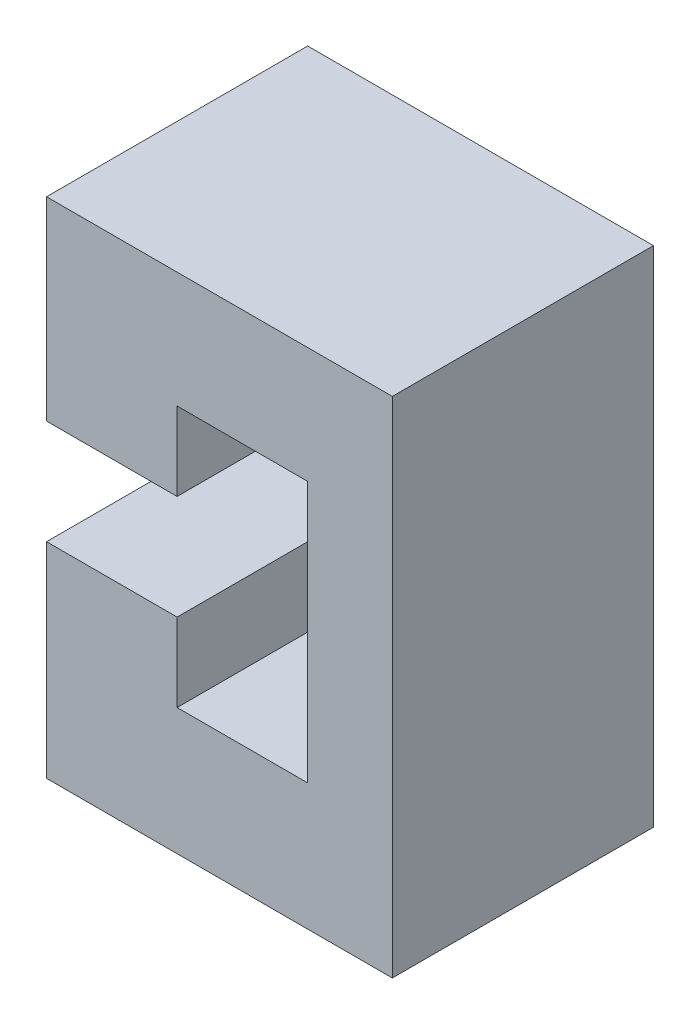
SolidWorks part; units mm, degrees
material "PLA"
ref_plane "Front Plane" through (0, 0, 0) normal (0, 0, 1) x (1, 0, 0)
ref_plane "Top Plane" through (0, 0, 0) normal (0, 1, 0) x (1, 0, 0)
ref_plane "Right Plane" through (0, 0, 0) normal (1, 0, 0) x (0, 0, -1)
sketch "Sketch1" plane through (0, 0, 0) normal (0, 0, 1) x (1, 0, 0)
  line L0 (-77.6365, -36.821) -> (-77.6365, -44.6706)
  line L31 (-77.6365, -32.821) -> (-72.6365, -32.821)
  line L32 (-72.6365, -32.821) -> (-72.6365, -29.821)
  line L33 (-72.6365, -29.821) -> (-67.6365, -29.821)
  line L34 (-67.6365, -29.821) -> (-67.6365, -39.821)
  line L35 (-67.6365, -39.821) -> (-72.6365, -39.821)
  line L36 (-72.6365, -39.821) -> (-72.6365, -36.821)
  line L37 (-72.6365, -36.821) -> (-77.6365, -36.821)
  line L38 (-77.6365, -44.6706) -> (-64.3944, -44.6706)
  line L39 (-64.3944, -44.6706) -> (-64.3944, -25.381)
  line L40 (-64.3944, -25.381) -> (-77.6365, -25.381)
  line L41 (-77.6365, -25.381) -> (-77.6365, -32.821)
  dimension "D1" = 5
  dimension "D2" = 5
  dimension "D3" = 3
  dimension "D4" = 10
extrude "Boss-Extrude1" add sketch "Sketch1" along normal blind 10
